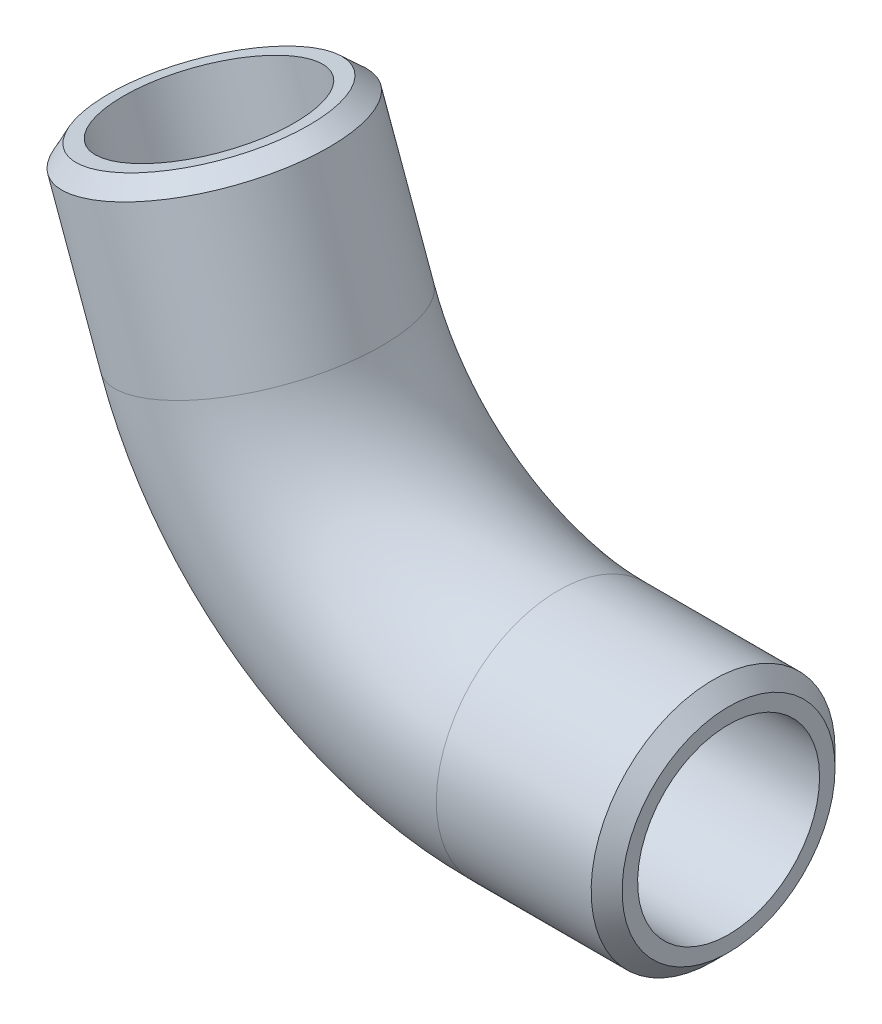
SolidWorks part; units mm, degrees
ref_plane "Plan de face" through (0, 0, 0) normal (0, 0, 1) x (1, 0, 0)
ref_plane "Plan de dessus" through (0, 0, 0) normal (0, 1, 0) x (1, 0, 0)
ref_plane "Plan de droite" through (0, 0, 0) normal (1, 0, 0) x (0, 0, -1)
sketch "Esquisse1" plane through (0, 0, 0) normal (0, 0, 1) x (1, 0, 0)
  line L0 (-21.9917, 0) -> (0, 0)
  line L1 (-59.5794, 26.3192) -> (-67.101, 46.9846)
  arc A0 (-21.9917, 0) -> (-59.5794, 26.3192) centre (-21.9917, 40) cw
  point P4 (0, 0)
  point P8 (-50, 0)
  dimension "D4" = 40
  dimension "D1" = 110
  dimension "D2" = 50
  dimension "D3" = 50
sketch "Esquisse2" plane through (0, 0, 0) normal (1, 0, 0) x (0, 0, -1)
  circle A0 centre (0, 0) radius 11.75
  circle A2 centre (0, 0) radius 15.75
  dimension "D1" = 23.5
  dimension "D2" = 4
sweep "Balayage2" add profiles "Esquisse2" path "Esquisse1"
chamfer "Chanfrein1" distance 2 angle 45 2 edges at (0, 0, -15.75) (-67.101, 46.9846, -15.75)
